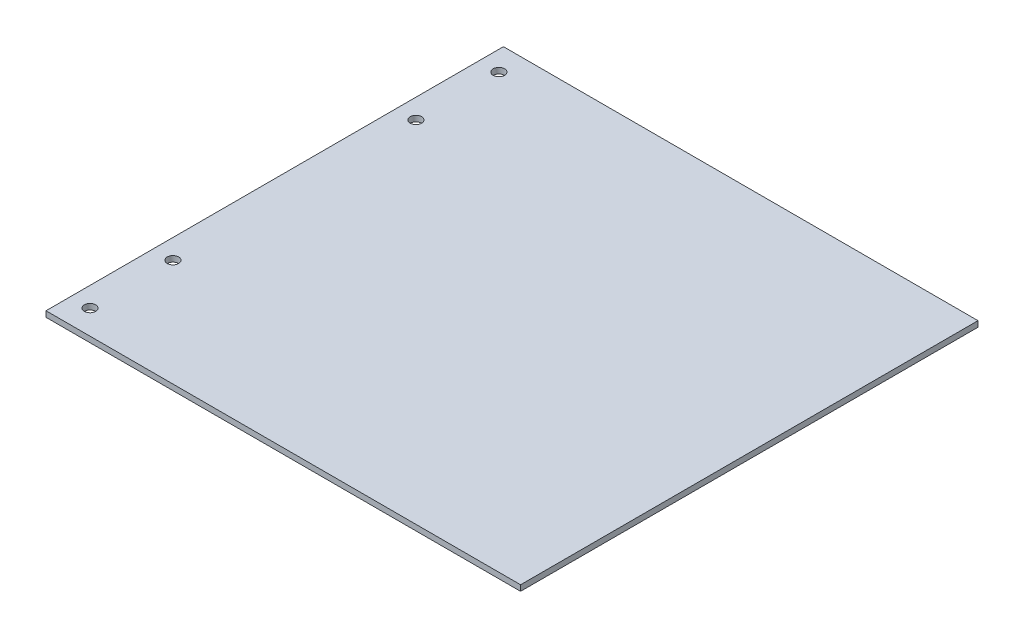
SolidWorks part; units mm, degrees
ref_plane "前视基准面" through (0, 0, 0) normal (0, 0, 1) x (1, 0, 0)
ref_plane "上视基准面" through (0, 0, 0) normal (0, 1, 0) x (1, 0, 0)
ref_plane "右视基准面" through (0, 0, 0) normal (1, 0, 0) x (0, 0, -1)
sketch "草图1" plane through (0, 0, 0) normal (0, 1, 0) x (1, 0, 0)
  line L1 (83, -80) -> (-83, -80)
  line L2 (83, -80) -> (83, 80)
  line L3 (83, 80) -> (-83, 80)
  line L4 (-83, -80) -> (-83, 80)
  line L5 (83, -80) -> (-83, 80) construction
  line L6 (83, 80) -> (-83, -80) construction
  point P0 (0, 0)
  dimension "D1" = 160
  dimension "D2" = 166
extrude "凸台-拉伸1" add sketch "草图1" along normal blind 2
sketch "草图3" plane through (0, 2, 0) normal (0, 1, 0) x (1, 0, 0)
  text T0 "Door" font "汉仪长仿宋体" height 12
hole_wizard "大小mm 暗销孔2" positions "草图6" profile "草图7" hole size "Ø4.0" standard "IS"
sketch "草图6" plane through (45.6368, 2.8, 467.0593) normal (0, 1, 0) x (0.0785, 0, 0.9969)
  point P0 (-404.9499, -103.6569)
  point P3 (-403.8976, -90.2983)
  point P6 (-432.808, -88.0209)
  point P9 (-433.8603, -101.3796)
  point P12 (-547.5083, -92.4273)
  point P15 (-518.5978, -94.7046)
  point P18 (-517.5455, -81.346)
  point P21 (-546.456, -79.0687)
sketch "草图7" plane through (-89.5, 2.8, 71.5) normal (1, 0, 0) x (0, 0, 1)
  line L0 (0, 0) -> (0, 11.2017)
  line L1 (0, 11.2017) -> (2, 10)
  line L2 (2, 10) -> (2, 0)
  line L3 (2, 0) -> (0, 0)
  line L4 (0, 11.2017) -> (-2, 10) construction
  line L5 (0, -6.35) -> (0, 107.95) construction
  dimension "孔直径" = 4
  dimension "孔深度" = 10
  dimension "导头角度" = 118
